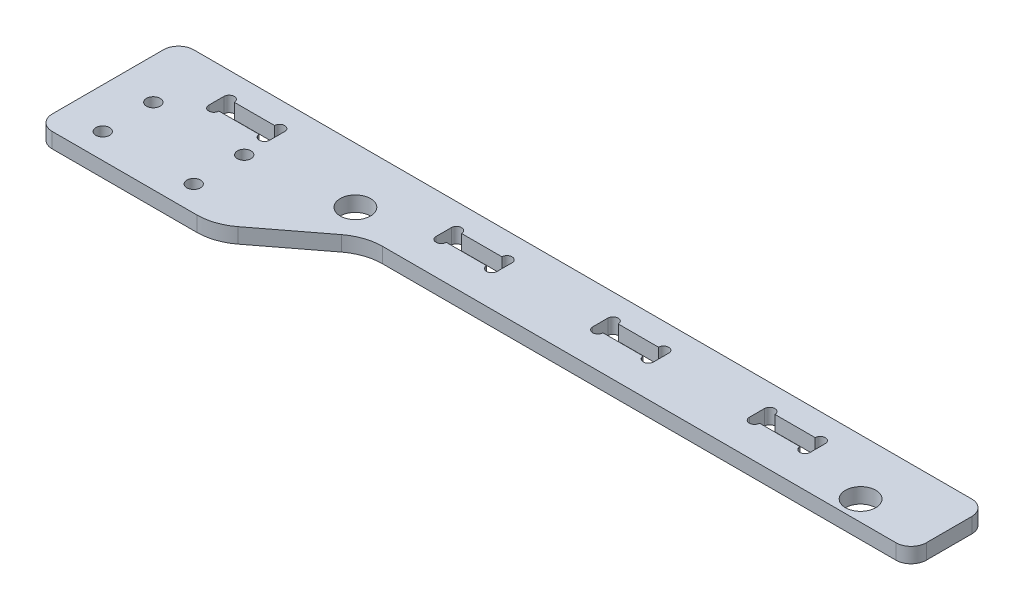
SolidWorks part; units mm, degrees
material "碳纤维"
ref_plane "前视基准面" through (0, 0, 0) normal (0, 0, 1) x (1, 0, 0)
ref_plane "上视基准面" through (0, 0, 0) normal (0, 1, 0) x (1, 0, 0)
ref_plane "右视基准面" through (0, 0, 0) normal (1, 0, 0) x (0, 0, -1)
sketch "草图1" plane through (0, 0, 0) normal (0, 1, 0) x (1, 0, 0)
  line L1 (-80, -7.5) -> (80, -7.5)
  line L2 (-80, -7.5) -> (-80, 7.5)
  line L3 (-80, 7.5) -> (80, 7.5)
  line L4 (80, -7.5) -> (80, 7.5)
  line L5 (0, 7.5) -> (0, -7.5) construction
  line L6 (-80, 0) -> (80, 0) construction
  point P0 (0, 0)
  dimension "D1" = 160
  dimension "D2" = 15
extrude "凸台-拉伸1" add sketch "草图1" along normal blind 3
sketch "草图2" plane through (0, 3, 0) normal (0, 1, 0) x (1, 0, 0)
  line L1 (-80, -7.5) -> (-28, -7.5)
  line L2 (-80, -7.5) -> (-80, -20.5)
  line L3 (-80, -20.5) -> (-28, -20.5)
  line L4 (-28, -7.5) -> (-28, -20.5)
  line L5 (-54, -20.5) -> (-54, -7.5) construction
  line L6 (-80, -14) -> (-28, -14) construction
  line L7 (-28, -7.5) -> (-45, -20.5)
  line L8 (80, -7.5) -> (80, 7.5) construction
  point P96 (-54, -14)
  line M5 (-80, -7.5) -> (80, -7.5)
  dimension "D1" = 13
  dimension "D2" = 108
  dimension "D3" = 17
extrude "凸台-拉伸2" add sketch "草图2" against normal up to surface (3 mm away) contours L7 L2 L3 M5 up to face at (0, 0, 0)
sketch "草图3" plane through (0, 0, 0) normal (0, -1, 0) x (1, 0, 0)
  line L0 (80, -1) -> (-80, -1) construction
  line L1 (80, 7.5) -> (80, -7.5) construction
  line L2 (80, -7.5) -> (-80, -7.5) construction
  line L3 (22, 0.5) -> (22, -2.5)
  line L4 (53, 0.5) -> (41, 0.5)
  line L5 (53, 0.5) -> (53, -2.5)
  line L6 (53, -2.5) -> (41, -2.5)
  line L7 (41, 0.5) -> (41, -2.5)
  line L8 (47, -2.5) -> (47, 0.5) construction
  line L9 (53, -1) -> (41, -1) construction
  line L10 (22, 0.5) -> (10, 0.5)
  line L11 (10, 0.5) -> (10, -2.5)
  line L12 (22, -2.5) -> (10, -2.5)
  line L13 (-9, 0.5) -> (-9, -2.5)
  line L14 (-9, 0.5) -> (-21, 0.5)
  line L15 (-21, 0.5) -> (-21, -2.5)
  line L16 (-9, -2.5) -> (-21, -2.5)
  line L17 (-80, -7.5) -> (-80, 20.5) construction
  line L18 (-54, 0.5) -> (-66, 0.5)
  line L19 (-54, 0.5) -> (-54, -2.5)
  line L20 (-54, -2.5) -> (-66, -2.5)
  line L21 (-66, 0.5) -> (-66, -2.5)
  line L22 (-60, -2.5) -> (-60, 0.5) construction
  line L23 (-54, -1) -> (-66, -1) construction
  point P7 (47, -1)
  point P11 (-60, -1)
  dimension "D1" = 12
  dimension "D2" = 3
  dimension "D3" = 27
  dimension "D5" = 31
  dimension "D6" = 45
  dimension "D7" = 5
  dimension "D4" = 3
extrude "切除-拉伸1" cut sketch "草图3" against normal through all
sketch "草图4" plane through (0, 0, 0) normal (0, -1, 0) x (1, 0, 0)
  line L0 (47, 0.5) -> (47, 0) construction
  line L1 (53, 0.5) -> (41, 0.5) construction
  line L2 (53, -1) -> (41, -1) construction
  line L3 (53, -2.5) -> (53, 0.5) construction
  line L4 (41, -2.5) -> (53, -2.5) construction
  line L5 (16, 0.5) -> (16, 0) construction
  line L6 (41, 0.5) -> (41, -2.5) construction
  line L7 (-15, 0.5) -> (-15, 0) construction
  line L9 (-66, -2.5) -> (-54, -2.5) construction
  line L12 (-60, 0) -> (-60, 0.5) construction
  line L13 (-54, 0.5) -> (-66, 0.5) construction
  circle A0 centre (52, -2.5) radius 1
  circle A3 centre (42, -2.5) radius 1
  circle A4 centre (21, -2.5) radius 1
  circle A7 centre (11, -2.5) radius 1
  circle A8 centre (-10, -2.5) radius 1
  circle A11 centre (-20, -2.5) radius 1
  circle A12 centre (-65, -2.5) radius 1
  circle A15 centre (-55, -2.5) radius 1
  circle A16 centre (-55, 0.5) radius 1
  circle A17 centre (-65, 0.5) radius 1
  circle A18 centre (-20, 0.5) radius 1
  circle A19 centre (-10, 0.5) radius 1
  circle A20 centre (11, 0.5) radius 1
  circle A21 centre (21, 0.5) radius 1
  circle A22 centre (42, 0.5) radius 1
  circle A23 centre (52, 0.5) radius 1
  dimension "D2" = 2
  dimension "D3" = 31
  dimension "D1" = 3
extrude "切除-拉伸2" cut sketch "草图4" against normal through all
sketch "草图5" plane through (0, 0, 0) normal (0, -1, 0) x (1, 0, 0)
  line L0 (-54, -1) -> (-21, -1) construction
  line L1 (-54, -2.5) -> (-54, 0.5) construction
  line L2 (-21, 0.5) -> (-21, -2.5) construction
  line L3 (-37.5, -1) -> (-37.5, -7.5) construction
  line L4 (80, -7.5) -> (-80, -7.5) construction
  line L58 (19.9802, 0.52) -> (12.0198, 0.52)
  line L59 (9.98, 0.5) -> (9.98, -2.5)
  line L60 (12.0198, -2.52) -> (19.9802, -2.52)
  line L61 (22.02, -2.5) -> (22.02, 0.5)
  line L62 (53.02, -2.5) -> (53.02, 0.5)
  line L63 (50.9802, 0.52) -> (43.0198, 0.52)
  line L64 (40.98, 0.5) -> (40.98, -2.5)
  line L65 (43.0198, -2.52) -> (50.9802, -2.52)
  line L66 (53.02, -2.5) -> (53.02, 0.5)
  line L67 (50.9802, 0.52) -> (43.0198, 0.52)
  line L68 (40.98, 0.5) -> (40.98, -2.5)
  line L69 (43.0198, -2.52) -> (50.9802, -2.52)
  line L70 (-11.0198, 0.52) -> (-18.9802, 0.52)
  line L71 (-21.02, 0.5) -> (-21.02, -2.5)
  line L72 (-18.9802, -2.52) -> (-11.0198, -2.52)
  line L73 (-8.98, -2.5) -> (-8.98, 0.5)
  line L74 (-66.02, -2.5) -> (-66.02, 0.5)
  line L75 (-56.0198, -2.52) -> (-63.9802, -2.52)
  line L76 (-53.98, 0.5) -> (-53.98, -2.5)
  line L77 (-63.9802, 0.52) -> (-56.0198, 0.52)
  arc A39 (22.02, 0.5) -> (19.9802, 0.52) centre (21, 0.5) ccw
  arc A40 (12.0198, 0.52) -> (9.98, 0.5) centre (11, 0.5) ccw
  arc A41 (9.98, -2.5) -> (12.0198, -2.52) centre (11, -2.5) ccw
  arc A42 (19.9802, -2.52) -> (22.02, -2.5) centre (21, -2.5) ccw
  arc A43 (53.02, 0.5) -> (50.9802, 0.52) centre (52, 0.5) ccw
  arc A44 (50.9802, -2.52) -> (53.02, -2.5) centre (52, -2.5) ccw
  arc A45 (43.0198, 0.52) -> (40.98, 0.5) centre (42, 0.5) ccw
  arc A46 (40.98, -2.5) -> (43.0198, -2.52) centre (42, -2.5) ccw
  arc A47 (53.02, 0.5) -> (50.9802, 0.52) centre (52, 0.5) ccw
  arc A48 (50.9802, -2.52) -> (53.02, -2.5) centre (52, -2.5) ccw
  arc A49 (43.0198, 0.52) -> (40.98, 0.5) centre (42, 0.5) ccw
  arc A50 (40.98, -2.5) -> (43.0198, -2.52) centre (42, -2.5) ccw
  arc A51 (-8.98, 0.5) -> (-11.0198, 0.52) centre (-10, 0.5) ccw
  arc A52 (-18.9802, 0.52) -> (-21.02, 0.5) centre (-20, 0.5) ccw
  arc A53 (-21.02, -2.5) -> (-18.9802, -2.52) centre (-20, -2.5) ccw
  arc A54 (-11.0198, -2.52) -> (-8.98, -2.5) centre (-10, -2.5) ccw
  arc A55 (-63.9802, -2.52) -> (-66.02, -2.5) centre (-65, -2.5) cw
  arc A56 (-53.98, -2.5) -> (-56.0198, -2.52) centre (-55, -2.5) cw
  arc A57 (-56.0198, 0.52) -> (-53.98, 0.5) centre (-55, 0.5) cw
  arc A58 (-66.02, 0.5) -> (-63.9802, 0.52) centre (-65, 0.5) cw
  dimension "D3" = 3
  dimension "D2" = 31
  dimension "D1" = 0.02
extrude "切除-拉伸4" cut sketch "草图5" against normal through all
fillet "圆角1" radius 3 4 edges at (80, 1.5, 7.5) (-80, 1.5, 20.5) (-80, 1.5, -7.5) (80, 1.5, -7.5)
fillet "圆角2" radius 10 2 edges at (-45, 1.5, 20.5) (-28, 1.5, 7.5)
sketch "草图7" plane through (0, 0, 0) normal (0, -1, 0) x (1, 0, 0)
  line L0 (0, 0) -> (0, -7.5) construction
  line L1 (77, -7.5) -> (-77, -7.5) construction
  line L2 (-34, 3.5) -> (66, 3.5) construction
  circle A1 centre (66, 3.5) radius 3
  circle A3 centre (-34, 3.5) radius 3
  dimension "D6" = 6
  dimension "D3" = 11
  dimension "D4" = 34
  dimension "D5" = 100
extrude "切除-拉伸5" cut sketch "草图7" against normal through all
sketch "草图8" plane through (0, 0, 0) normal (0, -1, 0) x (1, 0, 0)
  line L0 (-63, 20.5) -> (-63, 0.5) construction
  line L5 (-77, 20.5) -> (-48.3853, 20.5) construction
  line L6 (-63, 10.5) -> (-80, 10.5) construction
  line L7 (-80, -4.5) -> (-80, 17.5) construction
  circle A0 centre (-72, 5.5) radius 1.35
  circle A1 centre (-72, 15.5) radius 1.35
  circle A2 centre (-54, 15.5) radius 1.35
  circle A3 centre (-54, 5.5) radius 1.35
  dimension "D4" = 2.7
  dimension "D1" = 20
  dimension "D2" = 18
  dimension "D3" = 10
  dimension "D5" = 17
extrude "切除-拉伸6" cut sketch "草图8" against normal through all
move or copy body "实体-移动/复制1" [suppressed] bodies to move or copy 113
